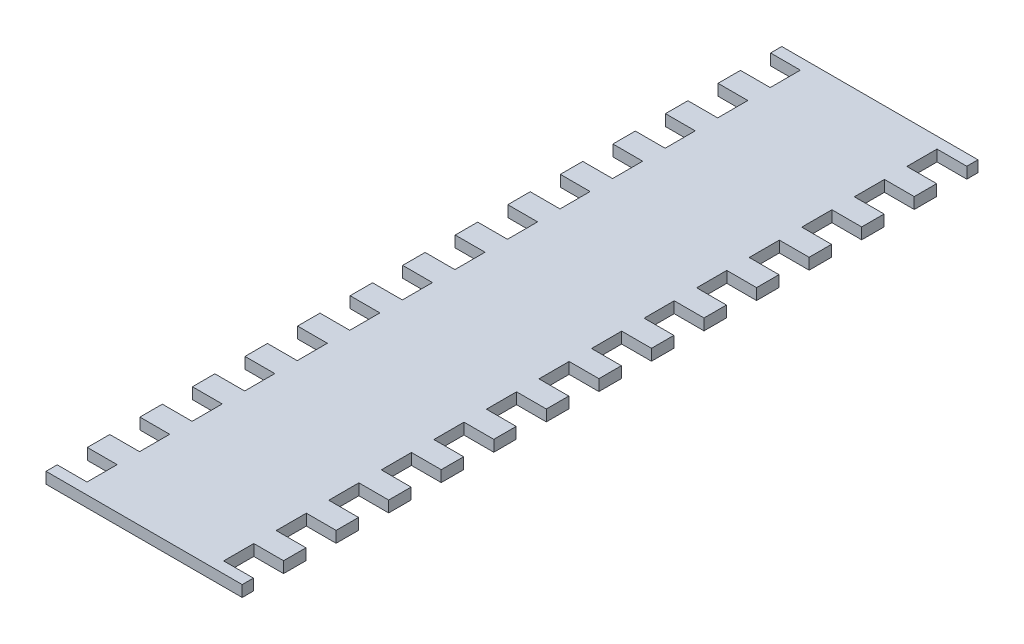
SolidWorks part; units mm, degrees
ref_plane "Front Plane" through (0, 0, 0) normal (0, 0, 1) x (1, 0, 0)
ref_plane "Top Plane" through (0, 0, 0) normal (0, 1, 0) x (1, 0, 0)
ref_plane "Right Plane" through (0, 0, 0) normal (1, 0, 0) x (0, 0, -1)
sketch "Sketch1" plane through (0, 0, 0) normal (0, 1, 0) x (1, 0, 0)
  line L0 (-8.25, 14.0337) -> (-8.25, -8.641) construction
  line L1 (14, -1.6) -> (-14, -1.6)
  line L2 (14, -1.6) -> (14, 1.6)
  line L3 (14, 1.6) -> (9.75, 1.6)
  line L4 (-14, -1.6) -> (-14, 1.6)
  line L5 (14, -1.6) -> (-14, 1.6) construction
  line L6 (14, 1.6) -> (-14, -1.6) construction
  line L8 (-9.75, 1.6) -> (-9.75, 5.9)
  line L10 (9.75, 1.6) -> (9.75, 5.9)
  line L11 (8.25, 14.0337) -> (8.25, -8.641) construction
  line L12 (-8.25, -8.641) -> (8.25, -8.641) construction
  line L14 (-9.75, 1.6) -> (-14, 1.6)
  line L15 (-9.75, 5.9) -> (-8.25, 5.9) construction
  line L16 (9.75, 5.9) -> (8.25, 5.9) construction
  line L17 (9.75, 5.9) -> (14, 5.9)
  line L18 (-9.75, 5.9) -> (-14, 5.9)
  line L19 (-9.75, 13.4) -> (-14, 13.4)
  line L20 (-9.75, 9.1) -> (-9.75, 13.4)
  line L21 (-9.75, 9.1) -> (-14, 9.1)
  line L22 (-14, 5.9) -> (-14, 9.1)
  line L23 (9.75, 9.1) -> (9.75, 13.4)
  line L24 (9.75, 13.4) -> (14, 13.4)
  line L25 (14, 9.1) -> (9.75, 9.1)
  line L26 (14, 5.9) -> (14, 9.1)
  line L27 (-9.75, 20.9) -> (-14, 20.9)
  line L28 (-9.75, 16.6) -> (-9.75, 20.9)
  line L29 (-9.75, 16.6) -> (-14, 16.6)
  line L30 (-14, 13.4) -> (-14, 16.6)
  line L31 (9.75, 16.6) -> (9.75, 20.9)
  line L32 (9.75, 20.9) -> (14, 20.9)
  line L33 (14, 16.6) -> (9.75, 16.6)
  line L34 (14, 13.4) -> (14, 16.6)
  line L35 (-9.75, 28.4) -> (-14, 28.4)
  line L36 (-9.75, 24.1) -> (-9.75, 28.4)
  line L37 (-9.75, 24.1) -> (-14, 24.1)
  line L38 (-14, 20.9) -> (-14, 24.1)
  line L39 (9.75, 24.1) -> (9.75, 28.4)
  line L40 (9.75, 28.4) -> (14, 28.4)
  line L41 (14, 24.1) -> (9.75, 24.1)
  line L42 (14, 20.9) -> (14, 24.1)
  line L43 (-9.75, 35.9) -> (-14, 35.9)
  line L44 (-9.75, 31.6) -> (-9.75, 35.9)
  line L45 (-9.75, 31.6) -> (-14, 31.6)
  line L46 (-14, 28.4) -> (-14, 31.6)
  line L47 (9.75, 31.6) -> (9.75, 35.9)
  line L48 (9.75, 35.9) -> (14, 35.9)
  line L49 (14, 31.6) -> (9.75, 31.6)
  line L50 (14, 28.4) -> (14, 31.6)
  line L51 (-9.75, 43.4) -> (-14, 43.4)
  line L52 (-9.75, 39.1) -> (-9.75, 43.4)
  line L53 (-9.75, 39.1) -> (-14, 39.1)
  line L54 (-14, 35.9) -> (-14, 39.1)
  line L55 (9.75, 39.1) -> (9.75, 43.4)
  line L56 (9.75, 43.4) -> (14, 43.4)
  line L57 (14, 39.1) -> (9.75, 39.1)
  line L58 (14, 35.9) -> (14, 39.1)
  line L59 (-9.75, 50.9) -> (-14, 50.9)
  line L60 (-9.75, 46.6) -> (-9.75, 50.9)
  line L61 (-9.75, 46.6) -> (-14, 46.6)
  line L62 (-14, 43.4) -> (-14, 46.6)
  line L63 (9.75, 46.6) -> (9.75, 50.9)
  line L64 (9.75, 50.9) -> (14, 50.9)
  line L65 (14, 46.6) -> (9.75, 46.6)
  line L66 (14, 43.4) -> (14, 46.6)
  line L67 (-9.75, 58.4) -> (-14, 58.4)
  line L68 (-9.75, 54.1) -> (-9.75, 58.4)
  line L69 (-9.75, 54.1) -> (-14, 54.1)
  line L70 (-14, 50.9) -> (-14, 54.1)
  line L71 (9.75, 54.1) -> (9.75, 58.4)
  line L72 (9.75, 58.4) -> (14, 58.4)
  line L73 (14, 54.1) -> (9.75, 54.1)
  line L74 (14, 50.9) -> (14, 54.1)
  line L75 (-9.75, 65.9) -> (-14, 65.9)
  line L76 (-9.75, 61.6) -> (-9.75, 65.9)
  line L77 (-9.75, 61.6) -> (-14, 61.6)
  line L78 (-14, 58.4) -> (-14, 61.6)
  line L79 (9.75, 61.6) -> (9.75, 65.9)
  line L80 (9.75, 65.9) -> (14, 65.9)
  line L81 (14, 61.6) -> (9.75, 61.6)
  line L82 (14, 58.4) -> (14, 61.6)
  line L83 (-9.75, 73.4) -> (-14, 73.4)
  line L84 (-9.75, 69.1) -> (-9.75, 73.4)
  line L85 (-9.75, 69.1) -> (-14, 69.1)
  line L86 (-14, 65.9) -> (-14, 69.1)
  line L87 (9.75, 69.1) -> (9.75, 73.4)
  line L88 (9.75, 73.4) -> (14, 73.4)
  line L89 (14, 69.1) -> (9.75, 69.1)
  line L90 (14, 65.9) -> (14, 69.1)
  line L91 (-9.75, 80.9) -> (-14, 80.9)
  line L92 (-9.75, 76.6) -> (-9.75, 80.9)
  line L93 (-9.75, 76.6) -> (-14, 76.6)
  line L94 (-14, 73.4) -> (-14, 76.6)
  line L95 (9.75, 76.6) -> (9.75, 80.9)
  line L96 (9.75, 80.9) -> (14, 80.9)
  line L97 (14, 76.6) -> (9.75, 76.6)
  line L98 (14, 73.4) -> (14, 76.6)
  line L99 (-9.75, 88.4) -> (-14, 88.4)
  line L100 (-9.75, 84.1) -> (-9.75, 88.4)
  line L101 (-9.75, 84.1) -> (-14, 84.1)
  line L102 (-14, 80.9) -> (-14, 84.1)
  line L103 (9.75, 84.1) -> (9.75, 88.4)
  line L104 (9.75, 88.4) -> (14, 88.4)
  line L105 (14, 84.1) -> (9.75, 84.1)
  line L106 (14, 80.9) -> (14, 84.1)
  line L107 (-9.75, 95.9) -> (-14, 95.9)
  line L108 (-9.75, 91.6) -> (-9.75, 95.9)
  line L109 (-9.75, 91.6) -> (-14, 91.6)
  line L110 (-14, 88.4) -> (-14, 91.6)
  line L111 (9.75, 91.6) -> (9.75, 95.9)
  line L112 (9.75, 95.9) -> (14, 95.9)
  line L113 (14, 91.6) -> (9.75, 91.6)
  line L114 (14, 88.4) -> (14, 91.6)
  line L115 (-9.75, 103.4) -> (-14, 103.4)
  line L116 (-9.75, 99.1) -> (-9.75, 103.4)
  line L117 (-9.75, 99.1) -> (-14, 99.1)
  line L118 (-14, 95.9) -> (-14, 99.1)
  line L119 (9.75, 99.1) -> (9.75, 103.4)
  line L120 (9.75, 103.4) -> (14, 103.4)
  line L121 (14, 99.1) -> (9.75, 99.1)
  line L122 (14, 95.9) -> (14, 99.1)
  line L123 (-14, 103.4) -> (-14, 106.6)
  line L124 (-14, 106.6) -> (14, 106.6)
  line L125 (14, 106.6) -> (14, 103.4)
  point P0 (0, 0)
  point P10 (0, 5.9)
  point P16 (0, -8.641)
  dimension "D1" = 7.5
  dimension "D2" = 3.2
  dimension "D3" = 4.3
  dimension "D4" = 28
  dimension "D5" = 16.5
  dimension "D6" = 1.5
  dimension "D8" = 19.5
  dimension "D7" = 14
extrude "Boss-Extrude1" add sketch "Sketch1" along normal blind 1.6
sketch "Sketch2" plane through (0, 1.6, 0) normal (0, 1, 0) x (1, 0, 0)
  line L0 (-14, -1.6) -> (14, -1.6) construction
  line L1 (-23.9294, 105) -> (25.8962, 105)
  line L2 (-23.9294, 105) -> (-23.9294, 0)
  line L3 (-23.9294, 0) -> (25.8962, 0)
  line L4 (25.8962, 105) -> (25.8962, 0)
  line L5 (14, 106.6) -> (-14, 106.6) construction
  dimension "D1" = 1.6
  dimension "D2" = 1.6
extrude "Cut-Extrude1" cut sketch "Sketch2" against normal through all both and the other way through all flip side to cut
